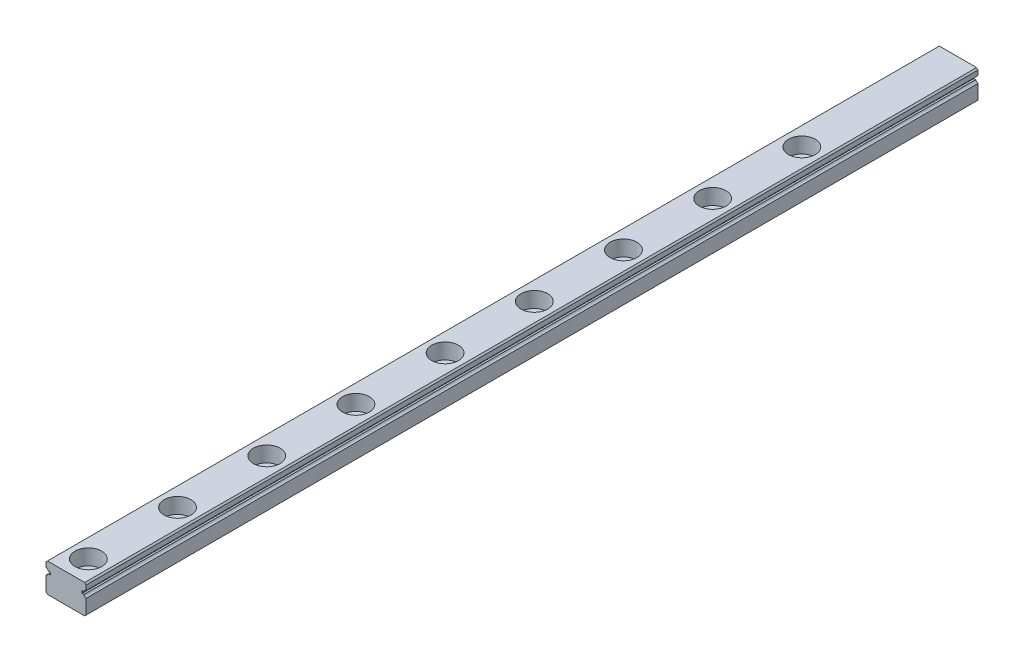
SolidWorks part; units mm, degrees
ref_plane "前视基准面" through (0, 0, 0) normal (0, 0, 1) x (1, 0, 0)
ref_plane "上视基准面" through (0, 0, 0) normal (0, 1, 0) x (1, 0, 0)
ref_plane "右视基准面" through (0, 0, 0) normal (1, 0, 0) x (0, 0, -1)
sketch "草图1" plane through (0, 0, 0) normal (0, 0, 1) x (1, 0, 0)
  line L0 (-1000, 0) -> (0, 0) construction
  line L1 (0, 0) -> (0, 4.2699) construction
  line L15 (-4.5, -2.9053) -> (-4.5, -6.1753)
  line L16 (-4.5, -6.1753) -> (-4.1747, -6.5005)
  line L19 (-4.1747, 0) -> (-4.5, -0.3253)
  line L20 (-4.5, -0.3253) -> (-4.5, -1.3953)
  line L23 (-3.5401, -1.9703) -> (-3.5401, -2.3303)
  line L27 (-4.1747, -6.5005) -> (0, -6.5005)
  line L37 (-3.6301, -1.8803) -> (-3.9901, -1.8803)
  line L38 (-3.6301, -2.4203) -> (-3.9901, -2.4203)
  line L40 (-4.1747, 0) -> (0, 0)
  line L41 (4.1747, 0) -> (0, 0)
  line L42 (3.6301, -2.4203) -> (3.9901, -2.4203)
  line L43 (3.6301, -1.8803) -> (3.9901, -1.8803)
  line L44 (4.1747, -6.5005) -> (0, -6.5005)
  line L45 (3.5401, -1.9703) -> (3.5401, -2.3303)
  line L46 (4.5, -0.3253) -> (4.5, -1.3953)
  line L47 (4.1747, 0) -> (4.5, -0.3253)
  line L48 (4.5, -6.1753) -> (4.1747, -6.5005)
  line L49 (4.5, -2.9053) -> (4.5, -6.1753)
  arc A1 (-4.5, -2.9053) -> (-3.9901, -2.4203) centre (-4.7325, -2.1503) ccw
  arc A2 (-3.5401, -1.9703) -> (-3.6301, -1.8803) centre (-3.6301, -1.9703) ccw
  arc A3 (-3.6301, -2.4203) -> (-3.5401, -2.3303) centre (-3.6301, -2.3303) ccw
  arc A4 (3.6301, -2.4203) -> (3.5401, -2.3303) centre (3.6301, -2.3303) cw
  arc A5 (3.5401, -1.9703) -> (3.6301, -1.8803) centre (3.6301, -1.9703) cw
  arc A6 (4.5, -2.9053) -> (3.9901, -2.4203) centre (4.7325, -2.1503) cw
  arc A7 (-3.9901, -1.8803) -> (-4.5, -1.3953) centre (-4.7325, -2.1503) ccw
  arc A8 (3.9901, -1.8803) -> (4.5, -1.3953) centre (4.7325, -2.1503) cw
  point P2 (-3.8101, -1.8803)
  point P16 (-3.8101, -2.4203)
  dimension "D9" = 1.51
  dimension "D10" = 1.58
  dimension "D13" = 0.18
  dimension "D14" = 0.09
  dimension "D6" = 0.09
  dimension "D7" = 0.79
  dimension "D16" = 135
  dimension "D22" = 0.54
  dimension "D2" = 9
  dimension "D3" = 135
  dimension "D4" = 135
  dimension "D5" = 0.46
  dimension "D8" = 1.07
  dimension "D11" = 0.54
  dimension "D12" = 0.27
  dimension "D15" = 0.36
  dimension "D17" = 0.46
  dimension "D18" = 135
  dimension "D19" = 9
  dimension "D20" = 3.27
  dimension "D21" = 0.36
  dimension "D23" = 0.27
extrude "凸台-拉伸1" add sketch "草图1" along normal blind 200
sketch "草图6" plane through (0, 0, 0) normal (0, 1, 0) x (1, 0, 0)
  line L0 (4.1747, -200) -> (-4.1747, -200) construction
  point P0 (0, -195)
  dimension "D1" = 5
hole_wizard "M2 六角头螺栓的柱形沉头孔1" positions "草图6" profile "草图4" counterbore size "M2" standard "GB" end condition up to next
sketch "草图4" plane through (0, 0, 195) normal (1, 0, 0) x (0, 0, 1)
  line L0 (0, 0) -> (0, 6.5005)
  line L1 (0, 6.5005) -> (1.2, 6.5005)
  line L3 (1.2, 6.5005) -> (1.2, 3.5)
  line L4 (1.2, 3.5) -> (3, 3.5)
  line L5 (3, 3.5) -> (3, 0)
  line L7 (3, 0) -> (0, 0)
  line L11 (0, -6.35) -> (0, 107.95) construction
  dimension "通孔孔直径" = 2.4
  dimension "通孔孔深度" = 6.5005
  dimension "柱形沉头孔直径" = 6
  dimension "柱形沉头孔深度" = 3.5
pattern_linear "阵列(线性)1" count 1 spacing 50 count 9 spacing 20 along (0, 0, -1) of "M2 六角头螺栓的柱形沉头孔1"
